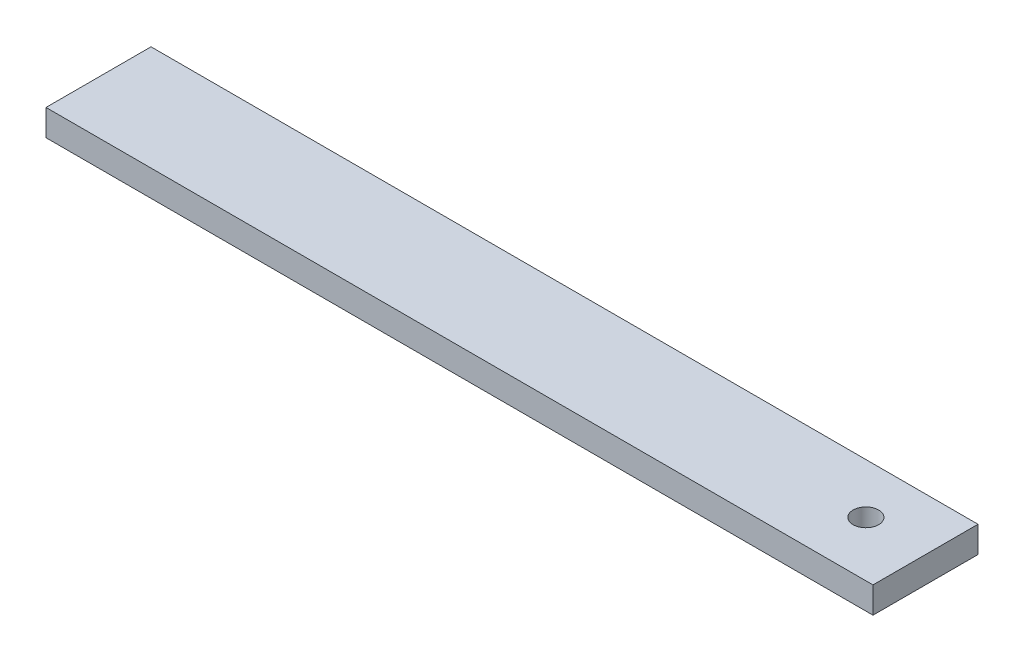
SolidWorks part; units mm, degrees
ref_plane "Front Plane" through (0, 0, 0) normal (0, 0, 1) x (1, 0, 0)
ref_plane "Top Plane" through (0, 0, 0) normal (0, 1, 0) x (1, 0, 0)
ref_plane "Right Plane" through (0, 0, 0) normal (1, 0, 0) x (0, 0, -1)
sketch "Sketch1" plane through (0, 0, 0) normal (0, 1, 0) x (1, 0, 0)
  line L1 (0, 0) -> (100, 0)
  line L2 (0, 0) -> (0, 12.7)
  line L3 (0, 12.7) -> (100, 12.7)
  line L4 (100, 0) -> (100, 12.7)
  circle A0 centre (92.5004, 6.6459) radius 1.5436
  dimension "D1" = 100
  dimension "D2" = 12.7
extrude "Boss-Extrude1" add sketch "Sketch1" along normal blind 3.175
